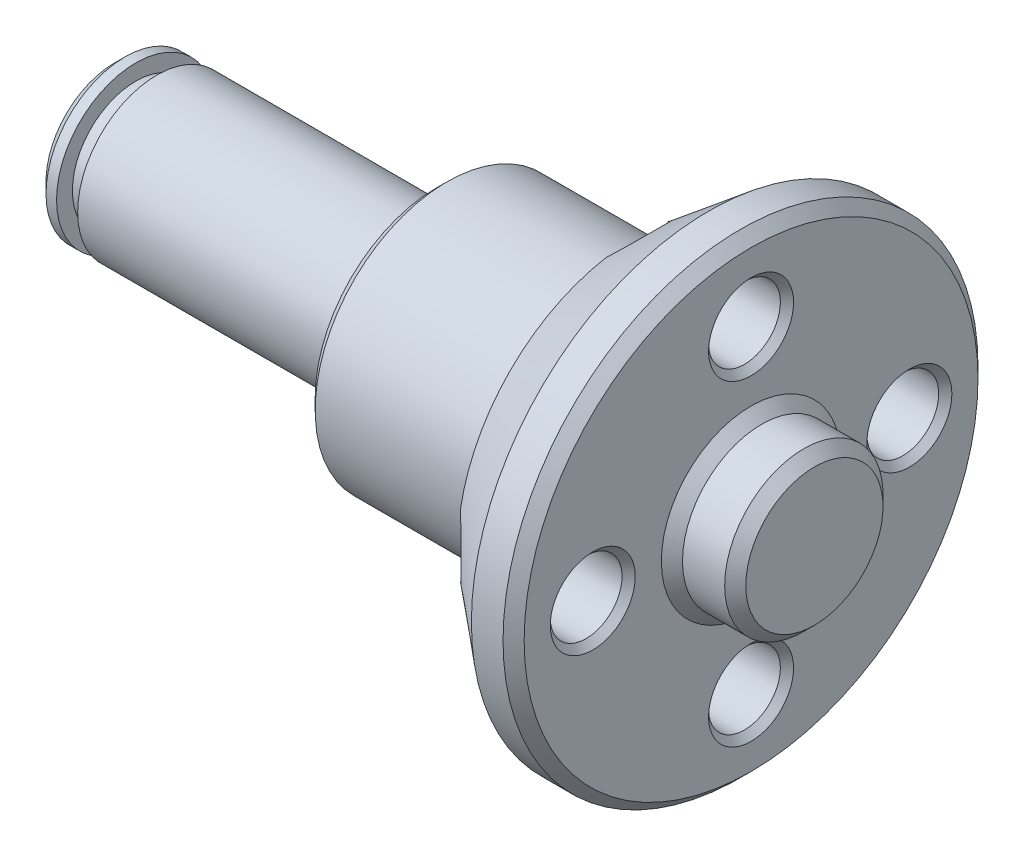
SolidWorks part; units mm, degrees
material "1.2210 (115CrV3)"
ref_plane "Front Plane" through (0, 0, 0) normal (0, 0, 1) x (1, 0, 0)
ref_plane "Top Plane" through (0, 0, 0) normal (0, 1, 0) x (1, 0, 0)
ref_plane "Right Plane" through (0, 0, 0) normal (1, 0, 0) x (0, 0, -1)
sketch "Sketch1" plane through (0, 0, 0) normal (0, 0, 1) x (1, 0, 0)
  line L0 (0, 0) -> (0, 7.5)
  line L1 (0, 7.5) -> (2, 7.5)
  line L2 (2, 7.5) -> (2, 6)
  line L3 (2, 6) -> (4, 6)
  line L4 (4, 6) -> (4, 7.5)
  line L5 (4, 7.5) -> (30.5, 7.5)
  line L6 (49.5, 12.5) -> (49.5, 17)
  line L7 (49.5, 17) -> (56.3, 17) construction
  line L8 (56.3, 17) -> (56.3, 22.5) construction
  line L9 (56.3, 22.5) -> (60.3, 22.5)
  line L10 (60.3, 22.5) -> (60.3, 7.5)
  line L11 (66.3, 0) -> (0, 0)
  line L12 (-14.4608, 0) -> (0, 0) construction
  line L13 (60.3, 7.5) -> (66.3, 7.5)
  line L14 (66.3, 7.5) -> (66.3, 0)
  line L15 (56.3, 22.5) -> (49.5, 17)
  line L16 (30.5, 7.5) -> (30.5, 12.5)
  line L17 (30.5, 12.5) -> (49.5, 12.5)
  dimension "D2" = 49.5
  dimension "D3" = 2
  dimension "D4" = 2
  dimension "D5" = 12
  dimension "D6" = 17
  dimension "D7" = 10.8
  dimension "D8" = 45
  dimension "D9" = 4
  dimension "D10" = 6
  dimension "D11" = 15
  dimension "D12" = 25
  dimension "D13" = 15
  dimension "D14" = 19
revolve "Revolve1" add sketch "Sketch1" angle 360 about L12
chamfer "Chamfer1" distance 1 angle 45 7 edges at (60.3, 0, 22.5) (0, 0, 7.5) (66.3, 0, 7.5) (60.3, 0, 7.5) (30.5, 0, 12.5) (49.5, 0, 12.5) (30.5, 0, 7.5)
hole_wizard "M8 Tapped Hole1" positions "Sketch4" profile "Sketch3" tap size "M8" standard "ISO"
sketch "Sketch4" plane through (60.3, 0, 0) normal (1, 0, 0) x (0, 0, -1)
  line L0 (-15, 0) -> (0, 15) construction
  line L1 (0, 15) -> (15, 0) construction
  line L2 (15, 0) -> (0, -15) construction
  line L3 (0, -15) -> (-15, 0) construction
  line L4 (-15, 0) -> (0, 0) construction
  line L5 (0, 0) -> (0, 15) construction
  line L6 (0, 15) -> (15, 0) construction
  line L7 (15, 0) -> (0, 0) construction
  line L8 (0, 0) -> (0, -15) construction
  point P0 (0, 15)
  point P2 (15, 0)
  point P4 (-15, 0)
  point P6 (0, -15)
  dimension "D1" = 15
  dimension "D2" = 90
sketch "Sketch3" plane through (60.3, 15, 0) normal (0, 1, 0) x (0, 0, -1)
  line L0 (0, 0) -> (0, 14.0429)
  line L1 (0, 14.0429) -> (3.4, 12)
  line L2 (3.4, 12) -> (3.4, 0.625)
  line L3 (3.4, 0.625) -> (4.025, 0)
  line L5 (4.025, 0) -> (0, 0)
  line L6 (-3.4, 0.625) -> (-4.025, 0) construction
  line L10 (0, 14.0429) -> (-3.4, 12) construction
  line L11 (0, -6.35) -> (0, 107.95) construction
  dimension "Tap Drill Dia." = 6.8
  dimension "Tap Drill Depth" = 12
  dimension "Near C'Sink Dia." = 8.05
  dimension "Near C'Sink Angle" = 90
  dimension "Drill Angle" = 118
